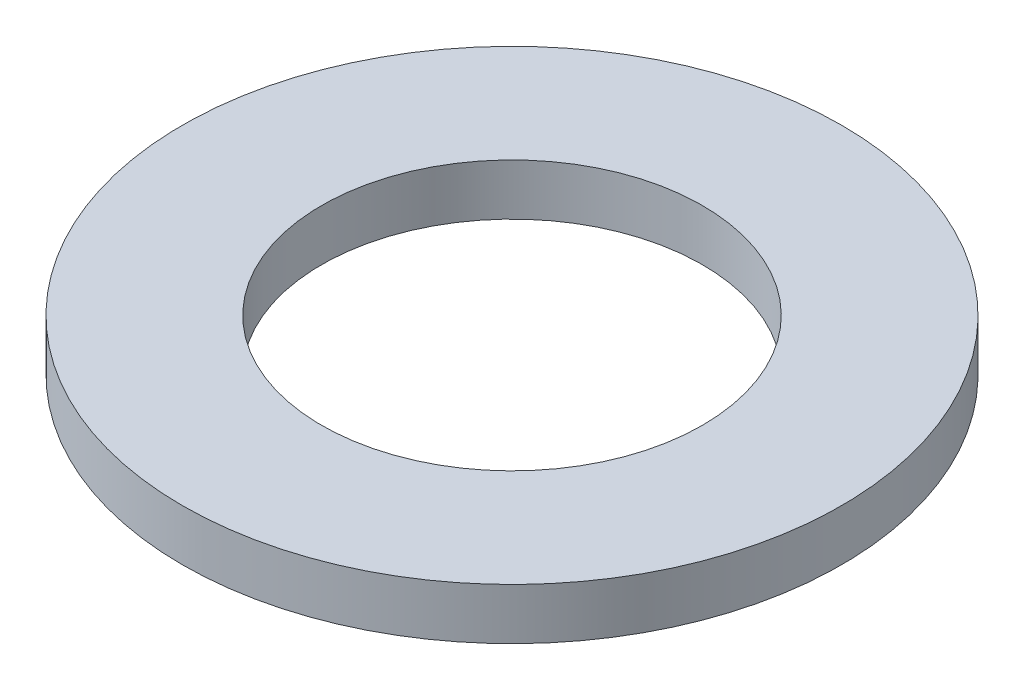
SolidWorks part; units mm, degrees
material "Plain Carbon Steel"
ref_plane "Front Plane" through (0, 0, 0) normal (0, 0, 1) x (1, 0, 0)
ref_plane "Top Plane" through (0, 0, 0) normal (0, 1, 0) x (1, 0, 0)
ref_plane "Right Plane" through (0, 0, 0) normal (1, 0, 0) x (0, 0, -1)
sketch "Sketch1" plane through (0, 0, 0) normal (0, 1, 0) x (1, 0, 0)
  circle A0 centre (0, 0) radius 4.5
  dimension "D1" = 9
extrude "Extrude-Thin1" add sketch "Sketch1" along normal blind 0.7 thin thin type one direction reverse wall 1.9
